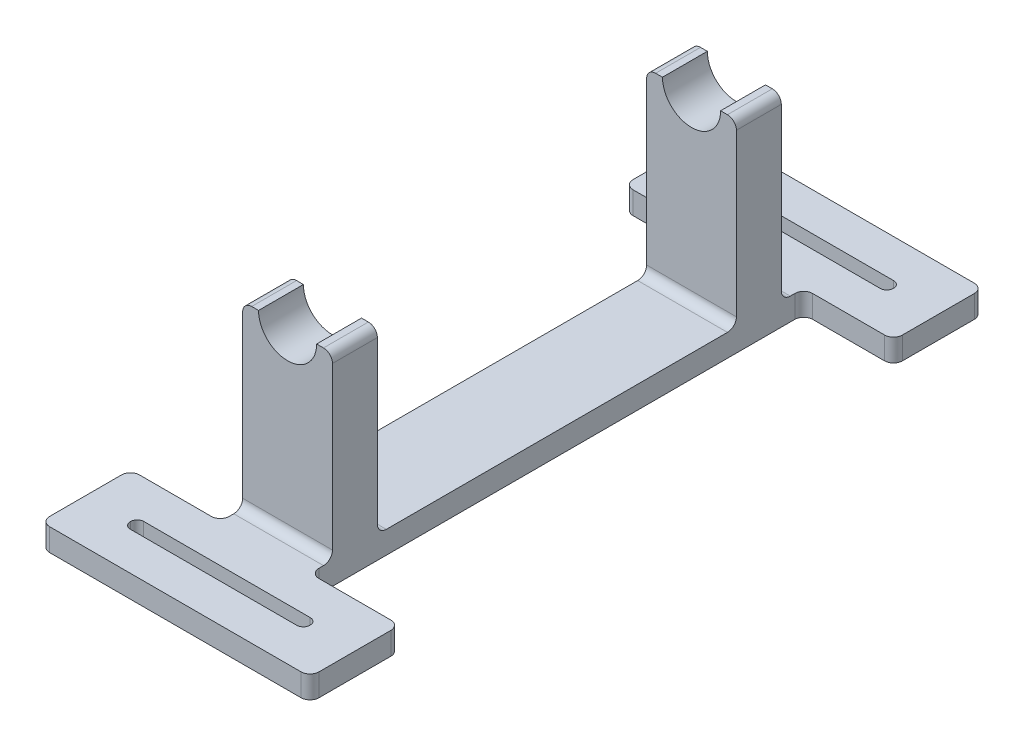
SolidWorks part; units mm, degrees
ref_plane "Front Plane" through (0, 0, 0) normal (0, 0, 1) x (1, 0, 0)
ref_plane "Top Plane" through (0, 0, 0) normal (0, 1, 0) x (1, 0, 0)
ref_plane "Right Plane" through (0, 0, 0) normal (1, 0, 0) x (0, 0, -1)
sketch "Sketch1" plane through (0, 0, 0) normal (0, 1, 0) x (1, 0, 0)
  line L0 (0.0004, -119.9264) -> (0.0004, 30.0736) construction
  line L1 (-29.9996, -119.9264) -> (30.0004, -119.9264)
  line L2 (-29.9996, -119.9264) -> (-29.9996, -99.9264)
  line L3 (-29.9996, 30.0736) -> (30.0004, 30.0736)
  line L4 (30.0004, -119.9264) -> (30.0004, -99.9264)
  line L5 (10.0004, -99.9264) -> (30.0004, -99.9264)
  line L6 (-9.9996, -99.9264) -> (-29.9996, -99.9264)
  line L7 (10.0004, 10.0736) -> (-9.9996, 10.0736) construction
  line L8 (10.0004, 10.0736) -> (10.0004, -99.9264)
  line L9 (10.0004, -99.9264) -> (-9.9996, -99.9264) construction
  line L10 (-9.9996, 10.0736) -> (-9.9996, -99.9264)
  line L11 (-29.9996, 30.0736) -> (-29.9996, 10.0736)
  line L12 (30.0004, 30.0736) -> (30.0004, 10.0736)
  line L13 (10.0004, 10.0736) -> (-9.9996, -99.9264) construction
  line L14 (10.0004, -99.9264) -> (-9.9996, 10.0736) construction
  line L15 (30.0004, 10.0736) -> (10.0004, 10.0736)
  line L16 (-9.9996, 10.0736) -> (-29.9996, 10.0736)
  point P9 (0.0004, -44.9264)
  dimension "D1" = 60
  dimension "D2" = 150
  dimension "D3" = 20
  dimension "D5" = 20
  dimension "D6" = 20
extrude "Boss-Extrude1" add sketch "Sketch1" along normal blind 5
sketch "Sketch2" plane through (0, 5, 0) normal (0, 1, 0) x (1, 0, 0)
  line L0 (-29.9996, 20.0736) -> (30.0004, 20.0736) construction
  line L1 (-29.9996, 30.0736) -> (-29.9996, 10.0736) construction
  line L2 (30.0004, 30.0736) -> (30.0004, 10.0736) construction
  line L8 (-29.9996, -109.9264) -> (30.0004, -109.9264) construction
  line L9 (-29.9996, -119.9264) -> (-29.9996, -99.9264) construction
  line L10 (30.0004, -119.9264) -> (30.0004, -99.9264) construction
  line L17 (-18.5492, 18.5736) -> (18.55, 18.5736)
  line L18 (-19.9992, 20.0236) -> (-19.9992, 20.1236)
  line L19 (-18.5492, 21.5736) -> (18.55, 21.5736)
  line L20 (20, 20.0236) -> (20, 20.1236)
  line L21 (-19.9992, 18.5736) -> (20, 21.5736) construction
  line L22 (-19.9992, 21.5736) -> (20, 18.5736) construction
  line L23 (-18.5496, -111.4264) -> (18.5504, -111.4264)
  line L24 (-19.9996, -109.9764) -> (-19.9996, -109.8764)
  line L25 (-18.5496, -108.4264) -> (18.5504, -108.4264)
  line L26 (20.0004, -109.9764) -> (20.0004, -109.8764)
  line L27 (-19.9996, -111.4264) -> (20.0004, -108.4264) construction
  line L28 (-19.9996, -108.4264) -> (20.0004, -111.4264) construction
  arc A0 (-18.5496, -111.4264) -> (-19.9996, -109.9764) centre (-18.5496, -109.9764) cw
  arc A1 (-19.9996, -109.8764) -> (-18.5496, -108.4264) centre (-18.5496, -109.8764) cw
  arc A2 (18.5504, -111.4264) -> (20.0004, -109.9764) centre (18.5504, -109.9764) ccw
  arc A3 (18.5504, -108.4264) -> (20.0004, -109.8764) centre (18.5504, -109.8764) cw
  arc A4 (18.55, 18.5736) -> (20, 20.0236) centre (18.55, 20.0236) ccw
  arc A5 (-18.5492, 18.5736) -> (-19.9992, 20.0236) centre (-18.5492, 20.0236) cw
  arc A6 (18.55, 21.5736) -> (20, 20.1236) centre (18.55, 20.1236) cw
  arc A7 (-19.9992, 20.1236) -> (-18.5492, 21.5736) centre (-18.5492, 20.1236) cw
  point P32 (0.0004, 20.0736)
  point P37 (0.0004, -109.9264)
  dimension "D3" = 1.45
  dimension "D1" = 3
  dimension "D2" = 3
  dimension "D4" = 10
extrude "Cut-Extrude1" cut sketch "Sketch2" against normal through all
sketch "Sketch3" plane through (0, 5, 0) normal (0, 1, 0) x (1, 0, 0)
  line L0 (10.0004, -44.9264) -> (-9.9996, -44.9264) construction
  line L1 (10.0004, 10.0736) -> (10.0004, -99.9264) construction
  line L2 (-9.9996, 10.0736) -> (-9.9996, -99.9264) construction
  line L3 (-9.9996, -4.9264) -> (10.0004, -4.9264)
  line L4 (10.0004, 5.0736) -> (-9.9996, 5.0736)
  line L5 (10.0004, 5.0736) -> (10.0004, -94.9264)
  line L6 (10.0004, -94.9264) -> (-9.9996, -94.9264)
  line L7 (-9.9996, 5.0736) -> (-9.9996, -94.9264)
  line L8 (10.0004, 5.0736) -> (-9.9996, -94.9264) construction
  line L9 (10.0004, -94.9264) -> (-9.9996, 5.0736) construction
  line L10 (-9.9996, -84.9264) -> (10.0004, -84.9264)
  point P6 (0.0004, -44.9264)
  point P12 (-9.7769, 8.4738)
  point P13 (9.8768, 8.4738)
  point P18 (0, 0)
  point P19 (0, 0)
  point P20 (0, 0)
  point P21 (0, 0)
  dimension "D1" = 10
  dimension "D2" = 10
  dimension "D3" = 100
  dimension "D4" = 20
extrude "Boss-Extrude2" add sketch "Sketch3" along normal blind 40
sketch "Sketch4" plane through (0, 0, -5.0736) normal (0, 0, -1) x (-1, 0, 0)
  line L0 (-10.0004, 45) -> (9.9996, 45) construction
  circle A0 centre (-0.0004, 45) radius 6.475
  dimension "D1" = 12.95
extrude "Cut-Extrude2" cut sketch "Sketch4" against normal through all
fillet "Fillet3" radius 2 19 edges at (10.0004, 45, -0.0736) (-9.9996, 45, -0.0736) (-9.9996, 45, 89.9264) (10.0004, 45, 89.9264) (-29.9996, 2.5, -10.0736) (-29.9996, 2.5, -30.0736) (30.0004, 2.5, -30.0736) (30.0004, 2.5, -10.0736) (10.0004, 2.5, -10.0736) (10.0004, 2.5, 99.9264) (30.0004, 2.5, 99.9264) (30.0004, 2.5, 119.9264) (-29.9996, 2.5, 119.9264) (-29.9996, 2.5, 99.9264) (-9.9996, 2.5, 99.9264) (0.0004, 5, 84.9264) (0.0004, 5, 94.9264) (0.0004, 5, 4.9264) (0.0004, 5, -5.0736)
